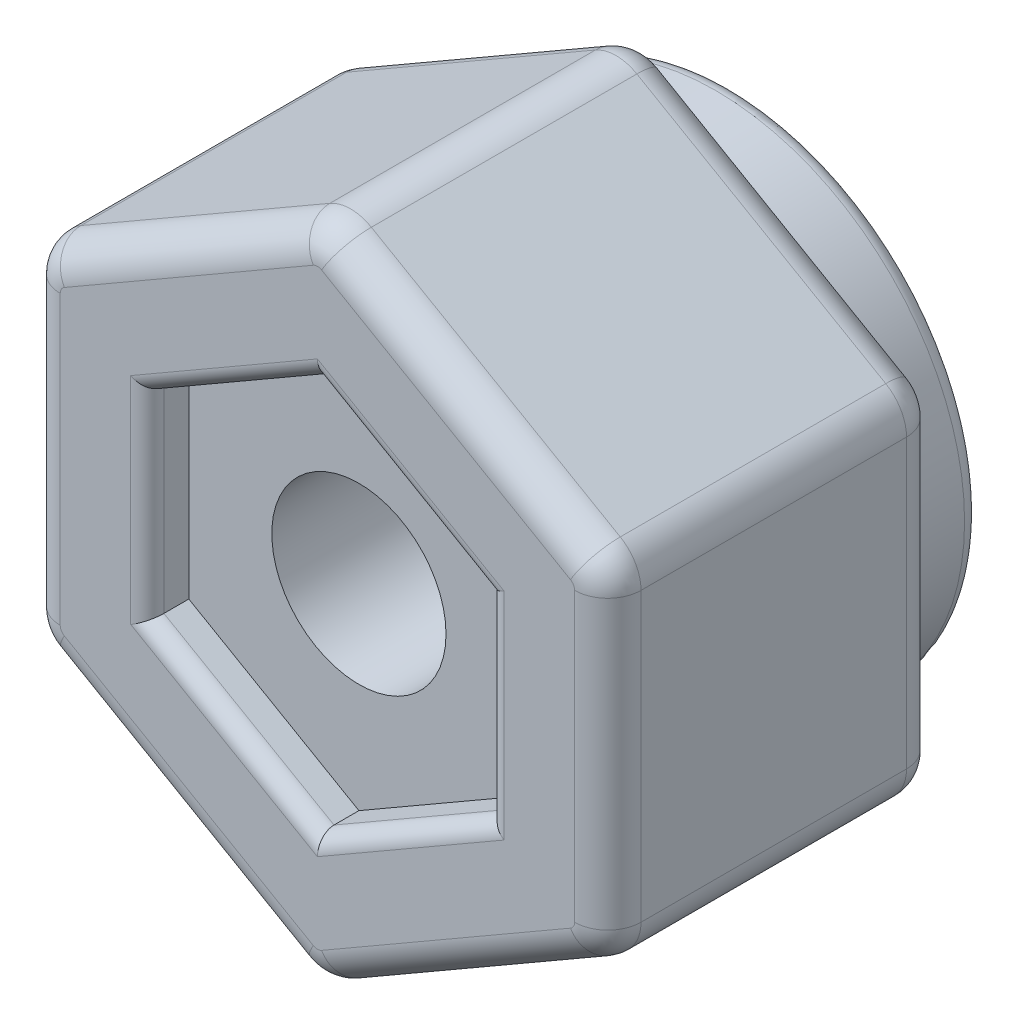
SolidWorks part; units mm, degrees
ref_plane "Přední rovina" through (0, 0, 0) normal (0, 0, 1) x (1, 0, 0)
ref_plane "Horní rovina" through (0, 0, 0) normal (0, 1, 0) x (1, 0, 0)
ref_plane "Pravá rovina" through (0, 0, 0) normal (1, 0, 0) x (0, 0, -1)
sketch "Sketch1" plane through (0, 0, 0) normal (0, 0, 1) x (1, 0, 0)
  line L1 (0, 8.0829) -> (-7, 4.0415)
  line L2 (-7, 4.0415) -> (-7, -4.0415)
  line L3 (-7, -4.0415) -> (0, -8.0829)
  line L4 (0, -8.0829) -> (7, -4.0415)
  line L5 (7, -4.0415) -> (7, 4.0415)
  line L6 (7, 4.0415) -> (0, 8.0829)
  circle A0 centre (0, 0) radius 7 construction
  dimension "D1" = 14
extrude "Boss-Extrude1" add sketch "Sketch1" along normal blind 8
sketch "Sketch2" plane through (0, 0, 8) normal (0, 0, 1) x (1, 0, 0)
  line L1 (0, 4.7343) -> (-4.1, 2.3671)
  line L2 (-4.1, 2.3671) -> (-4.1, -2.3671)
  line L3 (-4.1, -2.3671) -> (0, -4.7343)
  line L4 (0, -4.7343) -> (4.1, -2.3671)
  line L5 (4.1, -2.3671) -> (4.1, 2.3671)
  line L6 (4.1, 2.3671) -> (0, 4.7343)
  circle A0 centre (0, 0) radius 4.1 construction
  dimension "D1" = 8.2
extrude "Cut-Extrude1" cut sketch "Sketch2" against normal blind 1
sketch "Sketch3" plane through (0, 0, 7) normal (0, 0, 1) x (1, 0, 0)
  circle A0 centre (0, 0) radius 2.1
  dimension "D1" = 4.2
extrude "Cut-Extrude2" cut sketch "Sketch3" against normal blind 5
fillet "Fillet1" radius 1 6 edges at (7, -4.0415, 4) (0, -8.0829, 4) (-7, -4.0415, 4) (-7, 4.0415, 4) (0, 8.0829, 4) (7, 4.0415, 4)
fillet "Fillet2" radius 0.8 24 edges at (6.866, 3.9641, 8) (7, 0, 8) (6.866, -3.9641, 8) (3.5, -6.0622, 8) (0, -7.9282, 8) (-3.5, -6.0622, 8) (-6.866, -3.9641, 8) (-7, 0, 8) (-6.866, 3.9641, 8) (-3.5, 6.0622, 8) (0, 7.9282, 8) (6.866, 3.9641, 0) (7, 0, 0) (6.866, -3.9641, 0) (3.5, -6.0622, 0) (0, -7.9282, 0) (-3.5, -6.0622, 0) (-6.866, -3.9641, 0) (-7, 0, 0) (-6.866, 3.9641, 0) (-3.5, 6.0622, 0) (0, 7.9282, 0) (3.5, 6.0622, 8) (3.5, 6.0622, 0)
fillet "Fillet3" radius 0.4 6 edges at (-4.1, 0, 8) (-2.05, -3.5507, 8) (2.05, -3.5507, 8) (4.1, 0, 8) (2.05, 3.5507, 8) (-2.05, 3.5507, 8)
sketch "Sketch4" plane through (0, 0, 0) normal (0, 0, -1) x (-1, 0, 0)
  circle A0 centre (0, 0) radius 2.1 construction
  circle A1 centre (0, 0) radius 2.1
  circle A2 centre (0, 0) radius 6
  dimension "D1" = 12
extrude "Boss-Extrude2" add sketch "Sketch4" along normal blind 2
fillet "Fillet4" radius 0.4 2 edges at (-2.1, 0, -2) (-6, 0, -2)
sketch "Sketch5" plane through (0, 0, 7) normal (0, 0, 1) x (1, 0, 0)
  circle A0 centre (0, 0) radius 2.1 construction
  circle A1 centre (0, 0) radius 2.1
extrude "Boss-Extrude3" add sketch "Sketch5" against normal blind 0.4
sketch "Sketch6" plane through (0, 0, 7) normal (0, 0, 1) x (1, 0, 0)
  circle A0 centre (0, 0) radius 2.1
  dimension "D1" = 4.2
extrude "Cut-Extrude3" cut sketch "Sketch6" against normal through all
